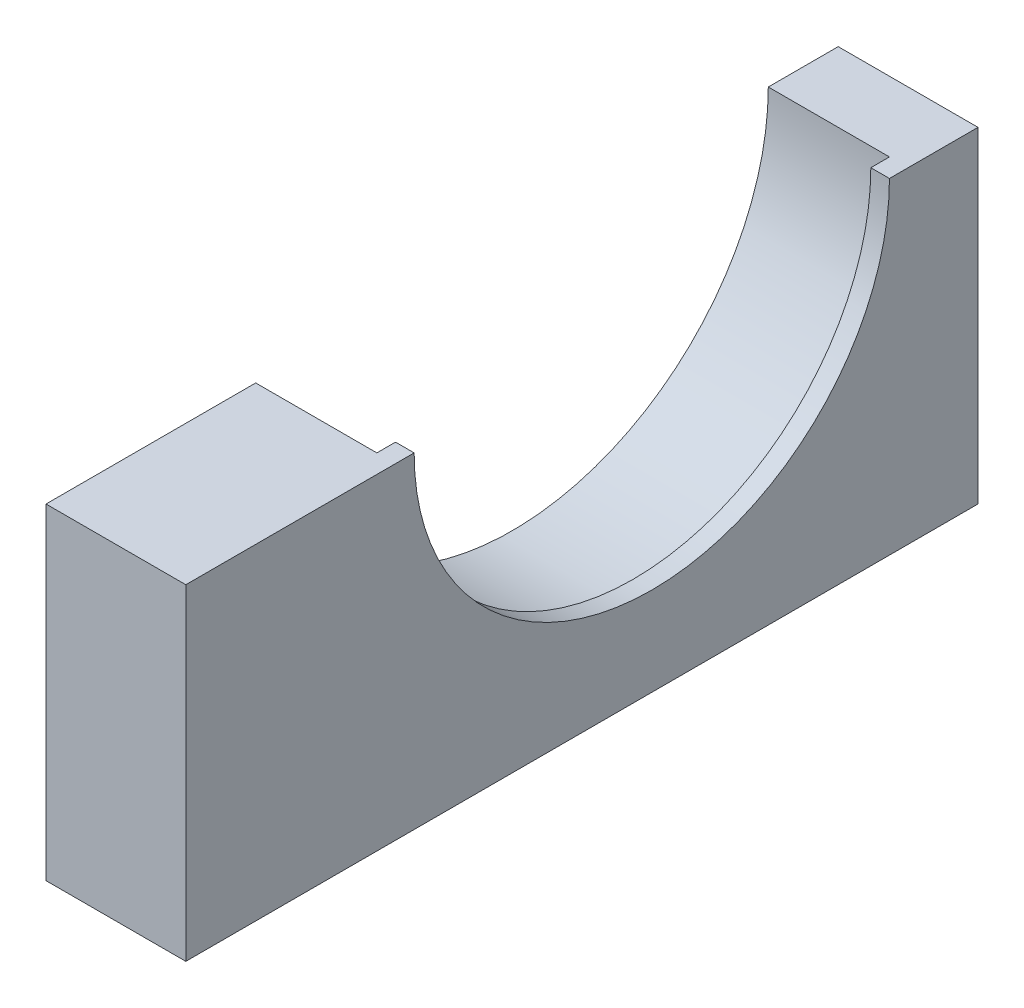
SolidWorks part; units mm, degrees
ref_plane "Front" through (0, 0, 0) normal (0, 0, 1) x (1, 0, 0)
ref_plane "Top" through (0, 0, 0) normal (0, 1, 0) x (1, 0, 0)
ref_plane "Right" through (0, 0, 0) normal (1, 0, 0) x (0, 0, -1)
sketch "Sketch1" plane through (0, 0, 0) normal (1, 0, 0) x (0, 0, -1)
  line L0 (-50, 0) -> (-27.5, 0)
  line L1 (-50, 0) -> (35, 0) construction
  line L2 (-50, 0) -> (-50, -35)
  line L3 (-50, -35) -> (35, -35)
  line L4 (35, 0) -> (35, -35)
  line L5 (27.5, 0) -> (35, 0)
  circle A0 centre (0, 0) radius 27.5 construction
  arc A1 (-27.5, 0) -> (27.5, 0) centre (0, 0) ccw
  dimension "D1" = 55
  dimension "D2" = 35
  dimension "D3" = 35
  dimension "D4" = 50
extrude "Boss-Extrude1" add sketch "Sketch1" along normal blind 13
sketch "Sketch4" plane through (13, 0, 0) normal (1, 0, 0) x (0, 0, -1)
  line L0 (35, 0) -> (35, -35)
  line L1 (35, -35) -> (-50, -35)
  line L2 (-50, -35) -> (-50, 0)
  line L3 (-50, 0) -> (-25.5, 0)
  line L4 (35, 0) -> (25.5, 0)
  arc A3 (-25.5, 0) -> (25.5, 0) centre (0, 0) ccw
  arc A4 (-25.5, 0) -> (25.5, 0) centre (0, 0) ccw
  point P8 (0, 0)
  point P12 (0, 0)
  dimension "D1" = 2
extrude "Boss-Extrude4" add sketch "Sketch4" along normal blind 2
